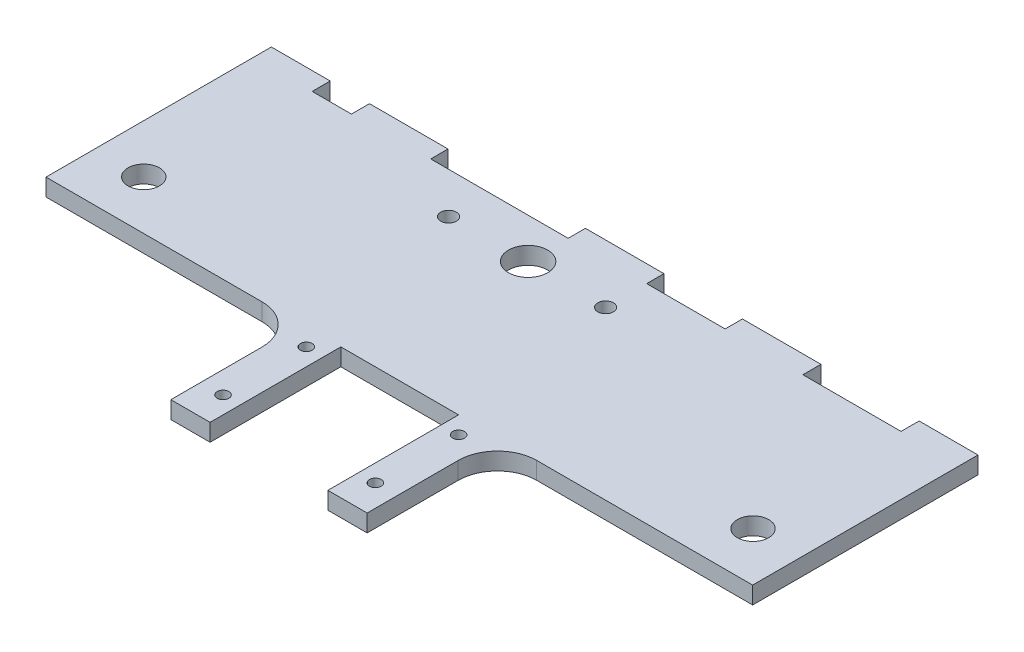
SolidWorks part; units mm, degrees
ref_plane "Front Plane" through (0, 0, 0) normal (0, 0, 1) x (1, 0, 0)
ref_plane "Top Plane" through (0, 0, 0) normal (0, 1, 0) x (1, 0, 0)
ref_plane "Right Plane" through (0, 0, 0) normal (1, 0, 0) x (0, 0, -1)
sketch "Sketch1" plane through (0, 0, 0) normal (0, 1, 0) x (1, 0, 0)
  line L0 (12.7, 67.056) -> (241.3, 67.056) construction
  line L3 (12.7, 72.898) -> (31.75, 72.898)
  line L5 (31.75, 72.898) -> (31.75, 67.056)
  line L6 (31.75, 67.056) -> (44.45, 67.056)
  line L7 (12.7, 0) -> (241.3, 0) construction
  line L8 (44.45, 67.056) -> (44.45, 72.898)
  line L10 (95.25, -42.164) -> (107.95, -42.164)
  line L12 (127, 0.1228) -> (146.05, 0.1228)
  line L13 (146.05, 0.1228) -> (146.05, -42.164)
  line L14 (127, 0.1228) -> (107.95, 0.1228)
  line L15 (107.95, 0.1228) -> (107.95, -42.164)
  line L16 (146.05, -42.164) -> (158.75, -42.164)
  line L17 (12.7, 0) -> (82.55, 0)
  line L18 (95.25, -12.7) -> (95.25, -42.164)
  line L19 (241.3, 0) -> (171.45, 0)
  line L20 (158.75, -12.7) -> (158.75, -42.164)
  line L27 (114.3, 72.898) -> (139.7, 72.898)
  line L28 (165.1, 72.898) -> (190.5, 72.898)
  line L29 (69.85, 72.898) -> (69.85, 67.31)
  line L30 (69.85, 67.31) -> (114.3, 67.31)
  line L31 (114.3, 67.31) -> (114.3, 72.898)
  line L32 (139.7, 72.898) -> (139.7, 67.31)
  line L33 (139.7, 67.31) -> (165.1, 67.31)
  line L34 (165.1, 67.31) -> (165.1, 72.898)
  line L35 (190.5, 72.898) -> (190.5, 67.056)
  line L36 (190.5, 67.056) -> (222.25, 67.056)
  line L37 (222.25, 67.056) -> (222.25, 72.898)
  line L38 (44.45, 72.898) -> (69.85, 72.898)
  line L39 (222.25, 72.898) -> (241.3, 72.898)
  line L40 (241.3, 72.898) -> (241.3, 0)
  line L41 (12.7, 72.898) -> (12.7, 0)
  arc A0 (171.45, 0) -> (158.75, -12.7) centre (171.45, -12.7) ccw
  arc A1 (95.25, -12.7) -> (82.55, 0) centre (82.55, -12.7) ccw
  point P0 (0, 0)
  point P10 (0, -41.181)
  point P27 (95.25, 0)
  dimension "D6" = 12.7
  dimension "D3" = 5.842
  dimension "D4" = 67.056
  dimension "D5" = 19.05
  dimension "D7" = 12.7
  dimension "D10" = 25.4
  dimension "D11" = 5.588
  dimension "D13" = 29.464
  dimension "D14" = 42.2868
  dimension "D15" = 12.7
  dimension "D17" = 25.4
  dimension "D20" = 228.6
extrude "Boss-Extrude1" add sketch "Sketch1" along normal blind 5.588
sketch "Sketch2" plane through (0, 0, 0) normal (0, -1, 0) x (1, 0, 0)
  point P0 (102.362, 32.3976)
  point P1 (151.638, 32.3976)
  point P3 (102.362, 5.4568)
  point P5 (151.638, 5.4568)
hole_wizard "#6 Clearance Hole1" positions "Sketch3" profile "Sketch4" hole size "#6" standard "ANSI Inch" end condition through all
sketch "Sketch3" plane through (0, 0, 0) normal (0, -1, 0) x (-1, 0, 0)
  point P0 (-102.362, -32.3976)
  point P3 (-151.638, -32.3976)
  point P6 (-151.638, -5.4568)
  point P9 (-102.362, -5.4568)
sketch "Sketch4" plane through (102.362, 0, 32.3976) normal (1, 0, 0) x (0, 0, -1)
  line L0 (0, 0) -> (0, 5.588)
  line L1 (0, 5.588) -> (1.8986, 5.588)
  line L2 (1.8986, 5.588) -> (1.8986, 0)
  line L5 (1.8986, 0) -> (0, 0)
  line L11 (0, -6.35) -> (0, 107.95) construction
  dimension "Thru Hole Dia." = 3.7973
  dimension "Thru Hole Depth" = 5.588
sketch "Sketch5" plane through (0, 5.588, 0) normal (0, 1, 0) x (1, 0, 0)
  circle A0 centre (225.552, 15.8708) radius 5.08
  circle A1 centre (28.448, 15.8708) radius 5.08
  dimension "D1" = 10.16
  dimension "D2" = 10.16
extrude "Cut-Extrude1" cut sketch "Sketch5" against normal up to next
sketch "Sketch6" plane through (0, 0, 0) normal (0, -1, 0) x (1, 0, 0)
  line L0 (12.7, -72.898) -> (12.7, 0) construction
  line L1 (44.45, -67.056) -> (31.75, -67.056) construction
  circle A0 centre (114.3, -54.356) radius 6.35
  dimension "D1" = 12.7
  dimension "D2" = 101.6
  dimension "D3" = 12.7
extrude "Cut-Extrude2" cut sketch "Sketch6" against normal up to next
sketch "Sketch7" plane through (0, 5.588, 0) normal (0, 1, 0) x (1, 0, 0)
  circle A0 centre (139.7, 54.0205) radius 2.54
  circle A1 centre (114.3, 54.356) radius 6.35 construction
  circle A2 centre (88.9, 54.0205) radius 2.54
  point P2 (0, 0)
  point P7 (95.4927, 54.356)
  dimension "D1" = 5.08
  dimension "D2" = 25.4
  dimension "D3" = 25.4
extrude "Cut-Extrude3" cut sketch "Sketch7" against normal up to next
sketch "Sketch8" plane through (0, 0, 0) normal (0, -1, 0) x (1, 0, 0)
  circle A0 centre (214.0408, -40.8989) radius 2.4916
  circle A1 centre (184.559, -40.8989) radius 2.948
  dimension "D1" = 4.9833
